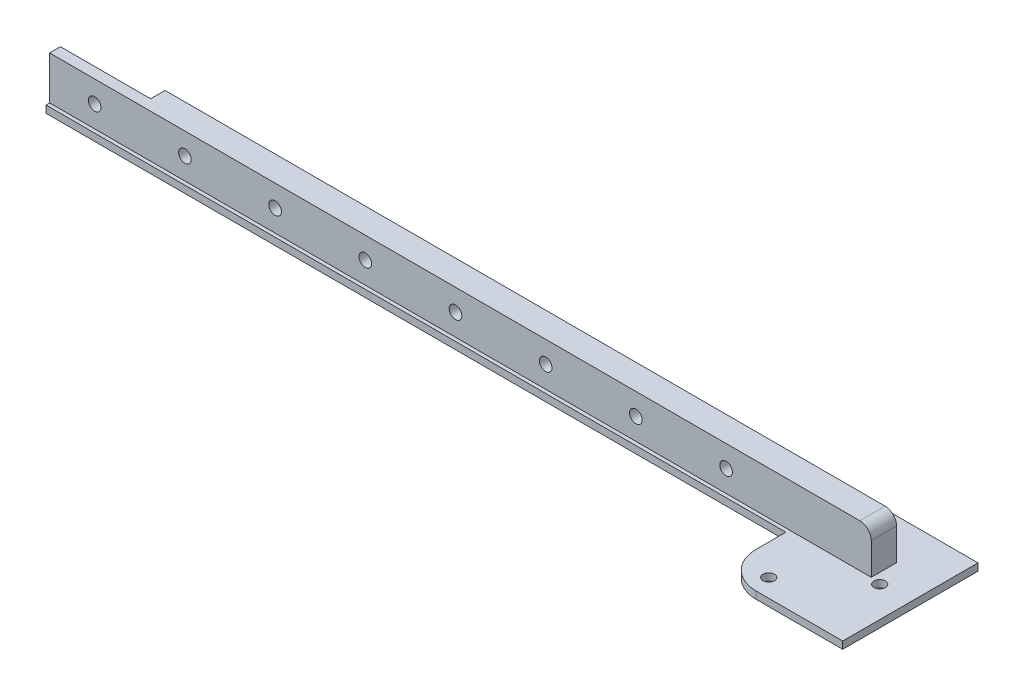
SolidWorks part; units mm, degrees
ref_plane "Front Plane" through (0, 0, 0) normal (0, 0, 1) x (1, 0, 0)
ref_plane "Top Plane" through (0, 0, 0) normal (0, 1, 0) x (1, 0, 0)
ref_plane "Right Plane" through (0, 0, 0) normal (1, 0, 0) x (0, 0, -1)
sketch "TopSketch1" plane through (0, 0, 0) normal (0, 1, 0) x (1, 0, 0)
  line L0 (0, 0) -> (34, 0)
  line L1 (34, 0) -> (34, 37.5)
  line L2 (34, 37.5) -> (0, 37.5)
  line L3 (0, 37.5) -> (0, 26.25)
  line L7 (0, 18.25) -> (0, 0)
  line L8 (0, 18.25) -> (-205.08, 18.25)
  line L9 (-205.08, 18.25) -> (-205.08, 26.25)
  line L10 (-205.08, 26.25) -> (0, 26.25)
  circle A0 centre (8.5, 32.5) radius 1.59
  circle A1 centre (8.5, 5) radius 1.59
  circle A3 centre (25.5, 18.75) radius 1.59
  dimension "D6" = 3.18
  dimension "D1" = 37.5
  dimension "D2" = 34
  dimension "D5" = 8.5
  dimension "D7" = 5
  dimension "D8" = 5
  dimension "D3" = 205.08
  dimension "D4" = 8
  dimension "D9" = 8.5
  dimension "D10" = 18.75
  dimension "D11" = 11.25
  dimension "D12" = 18.25
  dimension "D13" = 239.08
extrude "TopBoss-Extrude1" add sketch "TopSketch1" along normal blind 2
fillet "Fillet1" radius 10 2 edges at (0, 1, 0) (0, 1, -37.5)
sketch "LinearRailHEightSketch2" plane through (0, 2, 0) normal (0, 1, 0) x (1, 0, 0)
  line L0 (0, 26.25) -> (-205.08, 26.25) construction
  line L1 (-205.08, 26.25) -> (22.6667, 26.25)
  line L2 (-205.08, 26.25) -> (-205.08, 19.25)
  line L3 (-205.08, 19.25) -> (22.6667, 19.25)
  line L4 (22.6667, 26.25) -> (22.6667, 19.25)
  line L5 (-205.08, 26.25) -> (-205.08, 18.25) construction
  line L7 (-205.08, 18.25) -> (0, 18.25) construction
  line L8 (34, 0) -> (34, 37.5) construction
  dimension "D1" = 1
  dimension "D2" = 11.3333
extrude "LinearRailHeightBoss-Extrude2" add sketch "LinearRailHEightSketch2" along normal blind 12
sketch "LinearRailHolesSketch3" plane through (0, 0, -19.25) normal (0, 0, 1) x (1, 0, 0)
  line L0 (-205.08, 2) -> (22.6667, 2) construction
  line L1 (-205.08, 14) -> (-205.08, 2) construction
  circle A0 centre (-192.58, 8) radius 1.75
  circle A1 centre (-167.58, 8) radius 1.75
  circle A2 centre (-142.58, 8) radius 1.75
  circle A3 centre (-117.58, 8) radius 1.75
  circle A4 centre (-92.58, 8) radius 1.75
  circle A5 centre (-67.58, 8) radius 1.75
  circle A6 centre (-42.58, 8) radius 1.75
  circle A7 centre (-17.58, 8) radius 1.75
  dimension "D4" = 8
  dimension "D1" = 3.5
  dimension "D2" = 6
  dimension "D3" = 12.5
extrude "LinearRailHolesCut-Extrude1" cut sketch "LinearRailHolesSketch3" against normal through all
sketch "ConnectingPlateSketch2" plane through (0, 0, -26.25) normal (0, 0, -1) x (-1, 0, 0)
  line L0 (-22.6667, 14) -> (205.08, 14) construction
  line L1 (180.08, 14) -> (205.08, 14)
  line L2 (180.08, 14) -> (180.08, 0)
  line L3 (180.08, 0) -> (205.08, 0)
  line L4 (205.08, 14) -> (205.08, 0)
  dimension "D1" = 25
extrude "ConnectingPlateCut-Extrude1" cut sketch "ConnectingPlateSketch2" against normal blind 4
fillet "Fillet2" radius 3.175 1 edges at (22.6667, 14, -22.75)
equation "\"GABDepth\"= \"GABDistanceFromBackToFirstPulley\" + \"GABPulleyDDistanceBetween\" + \"GABDistanceFromPulleyToFront\""
equation "\"GABWidth\"= \"StandardWallThickness\" + \"GABDistanceFromLSideToPulley\" + \"GABPulleyWDistanceBetween\" + \"GABDistanceFromPulleyToRSide\""
equation "\"StandardWallThickness\"= 3mm"
equation "\"LinearRailWidth\"= 12mm'Spec"
equation "\"LinearRailHeight\"= 8mm'Spec"
equation "\"GABLRClampHoleOffsetFromSide\"= 5mm"
equation "\"GABDistanceFromBackToFirstPulley\"= 13.5mm"
equation "\"GABPulleyDDistanceBetween\"= 12.5mm'From the100"
equation "\"GABPulleyWDistanceBetween\"= 14.5mm'From the100"
equation "\"GABDistanceFromPulleyToFront\"= 8mm"
equation "\"GABDistanceFromLSideToPulley\"= 9.5mm + \"StandardWallThickness\""
equation "\"GABDistanceFromPulleyToRSide\"= 7.5mm"
equation "\"GABClampBaseHeight\"= 2mm"
equation "\"LinearRailHoleDiameter\"= 3.5mm'Spec"
equation "\"GABDistanceToFrontRearClampHoles\"= 8.5mm"
equation "\"D1@TopSketch1\" = \"GABWidth\""
equation "\"D2@TopSketch1\"=\"GABDepth\""
equation "\"D5@TopSketch1\" = \"GABDistanceToFrontRearClampHoles\""
equation "\"D7@TopSketch1\" = \"GABLRClampHoleOffsetFromSide\""
equation "\"D8@TopSketch1\" = \"GABLRClampHoleOffsetFromSide\""
equation "\"D1@TopBoss-Extrude1\" = \"GABClampBaseHeight\""
equation "\"RailThickness\"= .125in'Spec"
equation "\"D4@TopSketch1\"=\"LinearRailHeight\""
equation "\"D1@LinearRailHeightBoss-Extrude2\" = \"LinearRailWidth\""
equation "\"D1@LinearRailHolesSketch3\" = \"LinearRailHoleDiameter\""
equation "\"D2@LinearRailHolesSketch3\" = \"LinearRailWidth\" / 2"
equation "\"D9@TopSketch1\"=\"GABDistanceToFrontRearClampHoles\""
equation "\"D2@LinearRailHEightSketch2\"=\"GABDepth\"/3"
equation "\"D11@TopSketch1\"=(\"GABWidth\")/2 - \"LinearRailHeight\"+1/2"
equation "\"LinearRailHoleDistance\"= 25mm'Spec"
equation "\"D1@ConnectingPlateSketch2\" = \"LinearRailHoleDistance\""
equation "\"D1@ConnectingPlateCut-Extrude1\"=\"LinearRailHeight\"/2"
equation "\"D1@Fillet2\"=\"RailThickness\""
